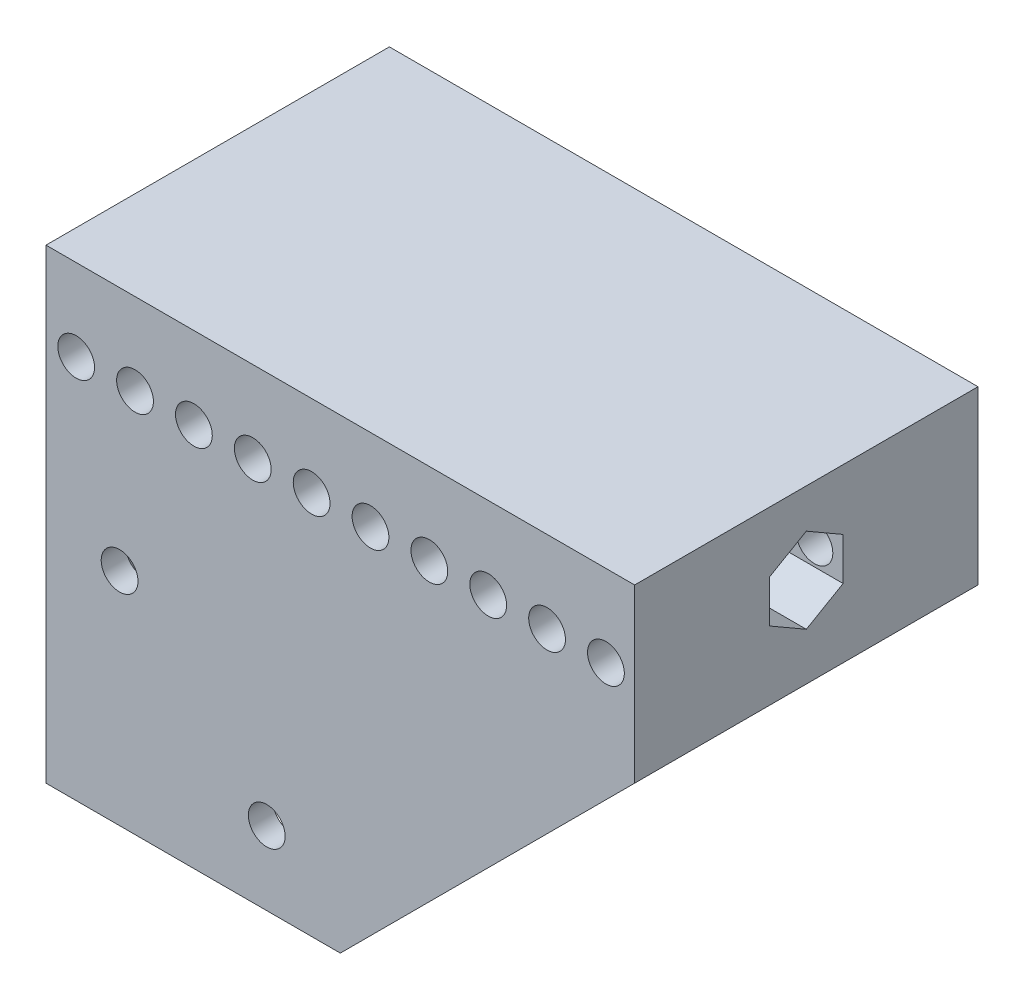
SolidWorks part; units mm, degrees
material "ABS"
ref_plane "Front Plane" through (0, 0, 0) normal (0, 0, 1) x (1, 0, 0)
ref_plane "Top Plane" through (0, 0, 0) normal (0, 1, 0) x (1, 0, 0)
ref_plane "Right Plane" through (0, 0, 0) normal (1, 0, 0) x (0, 0, -1)
sketch "Sketch1" plane through (0, 0, 0) normal (0, 0, 1) x (1, 0, 0)
  line L0 (0, 0) -> (38.1, 0)
  line L1 (38.1, 0) -> (76.2, 38.1)
  line L2 (76.2, 38.1) -> (0, 38.1)
  line L3 (0, 38.1) -> (0, 0)
  dimension "D1" = 76.2
  dimension "D2" = 38.1
  dimension "D3" = 38.1
extrude "Boss-Extrude1" add sketch "Sketch1" along normal blind 3.175
sketch "Sketch2" plane through (0, 0, 3.175) normal (0, 0, 1) x (1, 0, 0)
  line L0 (0, 38.1) -> (0, 0) construction
  line L1 (0, 38.1) -> (3.175, 38.1)
  line L2 (0, 38.1) -> (0, 0)
  line L3 (0, 0) -> (3.175, 0)
  line L4 (3.175, 38.1) -> (3.175, 0)
  line L5 (0, 0) -> (38.1, 0) construction
  line L6 (76.2, 38.1) -> (0, 38.1) construction
  dimension "D1" = 3.175
extrude "Boss-Extrude2" add sketch "Sketch2" along normal blind 41.275
ref_plane "Plane1" through (0, 0, 22.225) normal (0, 0, 1) x (1, 0, 0)
mirror "Mirror1" about plane through (0, 0, 22.225) normal (0, 0, 1) of "Boss-Extrude1"
sketch "Sketch3" plane through (0, 0, 0) normal (-1, 0, 0) x (0, 0, 1)
  line L0 (44.45, 38.1) -> (0, 38.1) construction
  line L1 (44.45, 38.1) -> (0, 38.1)
  line L2 (0, 38.1) -> (0, 60.325)
  line L4 (44.45, 60.325) -> (44.45, 38.1)
  line L6 (0, 60.325) -> (44.45, 60.325)
  point P12 (22.225, 60.325)
  dimension "D1" = 22.225
extrude "Boss-Extrude3" add sketch "Sketch3" against normal up to vertex (76.2 mm away)
ref_plane "Plane2" through (74.93, 0, 0) normal (1, 0, 0) x (0, 0, -1)
scale "Scale1" scale about centroid uniform scaling yes scale factor 1.333333
sketch "Sketch5" plane through (-11.685, 0, 0) normal (-1, 0, 0) x (0, 0, 1)
  line L0 (22.225, 51.7954) -> (22.225, 65.9029) construction
  line L1 (22.225, 51.7954) -> (22.225, 37.6878) construction
  line L2 (-7.4083, 37.6878) -> (51.8583, 37.6878) construction
  line L3 (51.8583, 65.9029) -> (51.8583, -14.5304) construction
  line L4 (22.225, 51.7954) -> (22.225, 59.1277) construction
  line L5 (28.575, 55.4615) -> (22.225, 59.1277)
  line L6 (22.225, 59.1277) -> (15.875, 55.4615)
  line L7 (15.875, 55.4615) -> (15.875, 48.1292)
  line L8 (15.875, 48.1292) -> (22.225, 44.463)
  line L9 (22.225, 44.463) -> (28.575, 48.1292)
  line L10 (28.575, 48.1292) -> (28.575, 55.4615)
  line L11 (51.8583, 65.9029) -> (-7.4083, 65.9029) construction
  circle A1 centre (22.225, 51.7954) radius 6.35 construction
  dimension "D1" = 12.7
  dimension "D2" = 28.2151
extrude "Cut-Extrude2" cut sketch "Sketch5" against normal through all both and the other way through all
sketch "Sketch6" plane through (0, 0, -7.4083) normal (0, 0, -1) x (-1, 0, 0)
  line L0 (-1.015, 23.5696) -> (-1.015, 36.2696) construction
  line L1 (-89.915, 36.2696) -> (-1.015, 36.2696) construction
  line L2 (11.685, 65.9029) -> (11.685, -14.5304) construction
  line L3 (11.685, -14.5304) -> (-39.115, -14.5304) construction
  line L7 (-26.415, -1.8304) -> (-26.415, -14.5304) construction
  circle A0 centre (-1.015, 23.5696) radius 3.175
  circle A1 centre (-26.415, -1.8304) radius 3.175
  dimension "D1" = 6.35
  dimension "D3" = 12.7
  dimension "D4" = 12.7
  dimension "D2" = 12.7
extrude "Cut-Extrude3" cut sketch "Sketch6" against normal through all both
sketch "Sketch7" plane through (-11.685, 0, 0) normal (-1, 0, 0) x (0, 0, 1)
  line L0 (7.4083, 37.0868) -> (7.4083, 24.3868) construction
  line L2 (-7.4083, 37.0868) -> (7.4083, 37.0868) construction
  line L3 (-7.4083, 65.9029) -> (-7.4083, -14.5304) construction
  line L4 (51.8583, 65.9029) -> (-7.4083, 65.9029) construction
  line L5 (37.0417, -1.8304) -> (37.0417, -14.5304) construction
  line L8 (37.0417, -14.5304) -> (51.8583, -14.5304) construction
  circle A1 centre (7.4083, 24.3868) radius 3.175
  circle A3 centre (37.0417, -1.8304) radius 3.175
  dimension "D1" = 6.35
  dimension "D2" = 14.8167
  dimension "D3" = 12.7
  dimension "D4" = 28.8162
extrude "Cut-Extrude4" cut sketch "Sketch7" against normal through all both
sketch "Sketch8" plane through (0, 0, 28.575) normal (0, 0, -1) x (-1, 0, 0)
  line L0 (-84.9626, 51.7954) -> (6.4774, 51.7954) construction
  line L3 (-84.9626, 51.7954) -> (-89.915, 51.7954) construction
  line L5 (6.4774, 51.7954) -> (11.685, 51.7954) construction
  line L7 (11.685, 55.4615) -> (11.685, 48.1292) construction
  line L8 (-89.915, 65.9029) -> (-89.915, 36.2696) construction
  circle A0 centre (-84.9626, 51.7954) radius 3.175
  circle A1 centre (-74.8026, 51.7954) radius 3.175
  circle A2 centre (-64.6426, 51.7954) radius 3.175
  circle A3 centre (-54.4826, 51.7954) radius 3.175
  circle A4 centre (-44.3226, 51.7954) radius 3.175
  circle A5 centre (-34.1626, 51.7954) radius 3.175
  circle A6 centre (-24.0026, 51.7954) radius 3.175
  circle A7 centre (-13.8426, 51.7954) radius 3.175
  circle A8 centre (-3.6826, 51.7954) radius 3.175
  circle A10 centre (6.4774, 51.7954) radius 3.175
  dimension "D3" = 10.16
  dimension "D4" = 10.16
  dimension "D5" = 10.16
  dimension "D6" = 10.16
  dimension "D7" = 10.16
  dimension "D8" = 10.16
  dimension "D9" = 10.16
  dimension "D10" = 10.16
  dimension "D11" = 10.16
  dimension "D2" = 6.35
  dimension "D12" = 4.9524
extrude "Cut-Extrude5" cut sketch "Sketch8" against normal through all both and the other way through all
